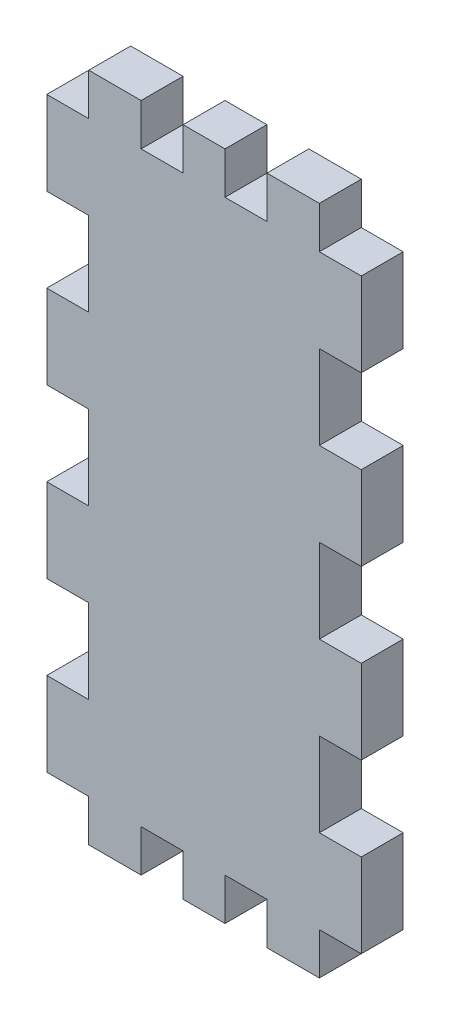
SolidWorks part; units mm, degrees
ref_plane "Front Plane" through (0, 0, 0) normal (0, 0, 1) x (1, 0, 0)
ref_plane "Top Plane" through (0, 0, 0) normal (0, 1, 0) x (1, 0, 0)
ref_plane "Right Plane" through (0, 0, 0) normal (1, 0, 0) x (0, 0, -1)
sketch "Sketch1" plane through (0, 0, 0) normal (0, 0, 1) x (1, 0, 0)
  line L1 (0, -170.3451) -> (-47.625, -170.3451)
  line L2 (0, -170.3451) -> (0, -68.7451)
  line L3 (0, -68.7451) -> (-47.625, -68.7451)
  line L4 (-47.625, -170.3451) -> (-47.625, -68.7451)
  dimension "D1" = 101.6
extrude "Boss-Extrude1" add sketch "Sketch1" against normal blind 6.35 contours L1 L4 L3 L2
sketch "Sketch3" plane through (0, 0, 0) normal (0, 0, 1) x (1, 0, 0)
  line L0 (-30.1625, -68.7451) -> (-17.4625, -68.7451) construction
  line L1 (0, -68.7451) -> (-47.625, -68.7451) construction
  line L2 (0, -170.3451) -> (-47.625, -170.3451) construction
  line L3 (-20.6375, -75.0951) -> (-14.2875, -75.0951)
  line L4 (-20.6375, -75.0951) -> (-20.6375, -62.3951)
  line L5 (-20.6375, -62.3951) -> (-14.2875, -62.3951)
  line L6 (-14.2875, -75.0951) -> (-14.2875, -62.3951)
  line L7 (-20.6375, -75.0951) -> (-14.2875, -62.3951) construction
  line L8 (-20.6375, -62.3951) -> (-14.2875, -75.0951) construction
  line L9 (-33.3375, -75.0951) -> (-26.9875, -75.0951)
  line L10 (-33.3375, -75.0951) -> (-33.3375, -62.3951)
  line L11 (-33.3375, -62.3951) -> (-26.9875, -62.3951)
  line L12 (-26.9875, -75.0951) -> (-26.9875, -62.3951)
  line L13 (-33.3375, -75.0951) -> (-26.9875, -62.3951) construction
  line L14 (-33.3375, -62.3951) -> (-26.9875, -75.0951) construction
  line L15 (-26.9875, -163.9951) -> (-33.3375, -163.9951)
  line L16 (-26.9875, -163.9951) -> (-26.9875, -176.6951)
  line L17 (-26.9875, -176.6951) -> (-33.3375, -176.6951)
  line L18 (-33.3375, -163.9951) -> (-33.3375, -176.6951)
  line L19 (-26.9875, -163.9951) -> (-33.3375, -176.6951) construction
  line L20 (-26.9875, -176.6951) -> (-33.3375, -163.9951) construction
  line L22 (-20.6375, -163.9951) -> (-14.2875, -163.9951)
  line L23 (-20.6375, -163.9951) -> (-20.6375, -176.6951)
  line L24 (-20.6375, -176.6951) -> (-14.2875, -176.6951)
  line L25 (-14.2875, -163.9951) -> (-14.2875, -176.6951)
  line L26 (-20.6375, -163.9951) -> (-14.2875, -176.6951) construction
  line L27 (-20.6375, -176.6951) -> (-14.2875, -163.9951) construction
  point P2 (-23.8125, -68.7451)
  point P13 (-30.1625, -170.3451)
  point P20 (-17.4625, -170.3451)
  dimension "D1" = 12.7
  dimension "D2" = 6.35
  dimension "D3" = 12.7
sketch "Sketch4" plane through (0, 0, 0) normal (0, 0, 1) x (1, 0, 0)
  line L0 (6.35, -125.8951) -> (-6.35, -113.1951) construction
  line L1 (6.35, -113.1951) -> (-6.35, -113.1951)
  line L2 (6.35, -113.1951) -> (6.35, -125.8951)
  line L3 (6.35, -125.8951) -> (-6.35, -125.8951)
  line L4 (-6.35, -113.1951) -> (-6.35, -125.8951)
  line L5 (-53.975, -113.1951) -> (-41.275, -113.1951)
  line L6 (-53.975, -113.1951) -> (-53.975, -125.8951)
  line L7 (-53.975, -125.8951) -> (-41.275, -125.8951)
  line L8 (-41.275, -113.1951) -> (-41.275, -125.8951)
  line L9 (0, -170.3451) -> (0, -68.7451) construction
  point P4 (0, -119.5451)
  dimension "D1" = 12.7
  dimension "D2" = 12.7
extrude "Cut-Extrude1" cut sketch "Sketch4" against normal through all
pattern_linear "LPattern1" count 3 spacing 25.4 along (0, -1, 0) count 3 spacing 25.4 along (0, 1, 0) of "Cut-Extrude1"
sketch "Sketch5" plane through (0, 0, 0) normal (0, 0, 1) x (1, 0, 0)
  line L1 (-23.8125, -160.8201) -> (-23.8125, -78.2701) construction
  line L2 (-23.8125, -138.5951) -> (-23.8125, -183.0451) construction
  line L3 (-15.875, -138.5951) -> (-15.875, -183.0451)
  line L4 (-31.75, -138.5951) -> (-31.75, -183.0451)
  line L5 (-23.8125, -100.4951) -> (-23.8125, -56.0451) construction
  line L6 (-31.75, -100.4951) -> (-31.75, -56.0451)
  line L7 (-15.875, -100.4951) -> (-15.875, -56.0451)
  arc A0 (-15.875, -138.5951) -> (-31.75, -138.5951) centre (-23.8125, -138.5951) ccw
  arc A1 (-31.75, -183.0451) -> (-15.875, -183.0451) centre (-23.8125, -183.0451) ccw
  arc A2 (-31.75, -100.4951) -> (-15.875, -100.4951) centre (-23.8125, -100.4951) ccw
  arc A3 (-15.875, -56.0451) -> (-31.75, -56.0451) centre (-23.8125, -56.0451) ccw
  point P6 (-23.8125, -119.5451)
  point P9 (-23.8125, -160.8201)
  point P16 (-23.8125, -78.2701)
  dimension "D2" = 44.45
  dimension "D3" = 7.9375
  dimension "D1" = 82.55
extrude "Weight savings" [suppressed] cut sketch "Sketch5" against normal through all
sketch "Sketch6" plane through (0, 0, -6.35) normal (0, 0, -1) x (-1, 0, 0)
  line L2 (30.1625, -152.8826) -> (17.4625, -152.8826)
  line L3 (30.1625, -152.8826) -> (30.1625, -146.5326)
  line L4 (30.1625, -146.5326) -> (17.4625, -146.5326)
  line L5 (17.4625, -152.8826) -> (17.4625, -146.5326)
  line L6 (30.1625, -152.8826) -> (17.4625, -146.5326) construction
  line L7 (30.1625, -146.5326) -> (17.4625, -152.8826) construction
  point P4 (23.8125, -149.7076)
  dimension "D1" = 6.35
  dimension "D2" = 12.7
extrude "Center Panel Mate" [suppressed] cut sketch "Sketch6" against normal through all
extrude "Cut-Extrude2" cut sketch "Sketch3" against normal through all
